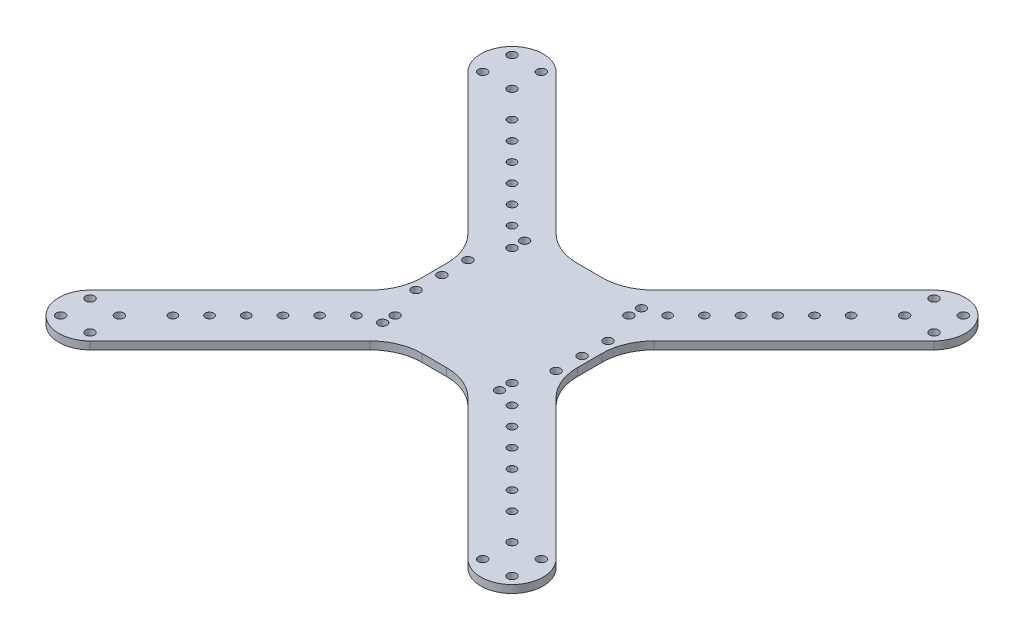
SolidWorks part; units mm, degrees
material "Carbon Fiber"
ref_plane "Front Plane" through (0, 0, 0) normal (0, 0, 1) x (1, 0, 0)
ref_plane "Top Plane" through (0, 0, 0) normal (0, 1, 0) x (1, 0, 0)
ref_plane "Right Plane" through (0, 0, 0) normal (1, 0, 0) x (0, 0, -1)
sketch "Sketch1" plane through (0, 0, 0) normal (0, 1, 0) x (1, 0, 0)
  line L0 (-81.3173, 81.3173) -> (81.3173, -81.3173) construction
  line L1 (-98.425, -98.425) -> (98.425, -98.425) construction
  line L2 (-98.425, -98.425) -> (-98.425, 98.425) construction
  line L3 (-98.425, 98.425) -> (98.425, 98.425) construction
  line L4 (98.425, -98.425) -> (98.425, 98.425) construction
  line L5 (-98.425, -98.425) -> (98.425, 98.425) construction
  line L6 (-98.425, 98.425) -> (98.425, -98.425) construction
  line L7 (-72.832, 89.8026) -> (-13.0294, 30)
  line L8 (-89.8026, 72.832) -> (-30, 13.0294)
  line L9 (0, 98.425) -> (0, -98.425) construction
  line L10 (81.3173, 81.3173) -> (-81.3173, -81.3173) construction
  line L11 (72.832, 89.8026) -> (13.0294, 30)
  line L12 (89.8026, 72.832) -> (30, 13.0294)
  line L13 (-30, -13.0294) -> (-89.8026, -72.832)
  line L14 (-13.0294, -30) -> (13.0294, -30)
  line L15 (-30, -13.0294) -> (-30, 13.0294)
  line L16 (-13.0294, 30) -> (13.0294, 30)
  line L17 (30, -13.0294) -> (30, 13.0294)
  line L18 (-30, -30) -> (30, 30) construction
  line L19 (-30, 30) -> (30, -30) construction
  line L20 (-13.0294, -30) -> (-72.832, -89.8026)
  line L21 (30, -13.0294) -> (89.8026, -72.832)
  line L22 (13.0294, -30) -> (72.832, -89.8026)
  arc A0 (-72.832, 89.8026) -> (-89.8026, 72.832) centre (-81.3173, 81.3173) ccw
  arc A1 (72.832, -89.8026) -> (89.8026, -72.832) centre (81.3173, -81.3173) ccw
  circle A2 centre (-81.3173, 81.3173) radius 8 construction
  circle A3 centre (81.3173, -81.3173) radius 8 construction
  circle A4 centre (-81.3173, -81.3173) radius 8 construction
  circle A5 centre (81.3173, 81.3173) radius 8 construction
  arc A6 (72.832, 89.8026) -> (89.8026, 72.832) centre (81.3173, 81.3173) cw
  arc A7 (-72.832, -89.8026) -> (-89.8026, -72.832) centre (-81.3173, -81.3173) cw
  point P0 (0, 0)
  point P8 (0, 0)
  point P23 (0, 0)
  point P29 (0, 0)
  point P42 (30, 0)
  dimension "D2" = 12
  dimension "D4" = 16
  dimension "D6" = 12
  dimension "D9" = 12
  dimension "D10" = 12
  dimension "D1" = 196.85
  dimension "D3" = 115
  dimension "D5" = 115
  dimension "D8" = 26.0589
  dimension "D11" = 30
  dimension "D12" = 30
extrude "Boss-Extrude1" add sketch "Sketch1" along normal blind 3
fillet "Fillet1" radius 20 8 edges at (-30, 1.5, -13.0294) (-30, 1.5, 13.0294) (-13.0294, 1.5, -30) (13.0294, 1.5, -30) (30, 1.5, 13.0294) (30, 1.5, -13.0294) (13.0294, 1.5, 30) (-13.0294, 1.5, 30)
ref_axis "Axis1" through (0, 6.3, 0) along (0, -1, 0)
ref_plane "Plane1" through (0, 0, 0) normal (-0.7071, 0, 0.7071) x (0, -1, 0)
sketch "Sketch2" plane through (0, 3, 0) normal (0, 1, 0) x (1, 0, 0)
  line L0 (0, 0) -> (-25, 0)
  line L1 (-25, 0) -> (-25, -25)
  line L2 (-25, -25) -> (0, -25)
  line L3 (0, -25) -> (0, 0)
  circle A1 centre (-22.525, -22.525) radius 1.7
  dimension "D4" = 3.4
  dimension "D1" = 25
  dimension "D2" = 22.525
  dimension "D3" = 22.525
extrude "Cut-Extrude1" cut sketch "Sketch2" against normal through all contours A1
pattern_circular "CirPattern1" count 4 over 360 about axis through (0, 0, 0) along (0, 1, 0) of "Cut-Extrude1"
sketch "Sketch3" plane through (0, 3, 0) normal (0, 1, 0) x (1, 0, 0)
  line L0 (0, 0) -> (-89.8026, -89.8026) construction
  circle A0 centre (-30, -30) radius 1.6
  arc A1 (-89.8026, -72.832) -> (-72.832, -89.8026) centre (-81.3173, -81.3173) ccw construction
  dimension "D1" = 3.2
  dimension "D2" = 30
extrude "Cut-Extrude2" cut sketch "Sketch3" against normal through all
pattern_linear "LPattern1" count 6 spacing 10 along (-0.7071, 0, 0.7071) of "Cut-Extrude2"
pattern_circular "CirPattern2" count 4 over 360 about axis through (0, 6.3, 0) along (0, -1, 0) of "LPattern1", "Cut-Extrude2"
sketch "Sketch4" plane through (0, 3, 0) normal (0, 1, 0) x (1, 0, 0)
  line L0 (-89.8026, -72.832) -> (-72.832, -89.8026) construction
  line L1 (-75.6604, -75.6604) -> (-86.9741, -86.9741) construction
  circle A0 centre (-81.3173, -81.3173) radius 8
  circle A1 centre (-86.9741, -86.9741) radius 1.7
  circle A2 centre (-86.9741, -75.6604) radius 1.7
  circle A3 centre (-75.6604, -75.6604) radius 1.7
  circle A4 centre (-75.6604, -86.9741) radius 1.7
  dimension "D1" = 16
  dimension "D2" = 3.4
extrude "Cut-Extrude3" cut sketch "Sketch4" against normal through all contours A0 A2 | A0 A2 | A0 A3 | A0 A3 | A0 A4 | A0 A4 | A0 A1 | A0 A1
pattern_circular "CirPattern3" count 4 over 360 about axis through (0, 0, 0) along (0, 1, 0) of "Cut-Extrude3"
sketch "Sketch5" plane through (0, 3, 0) normal (0, 1, 0) x (1, 0, 0)
  line L0 (-22.525, -22.525) -> (-22.525, 27.375) construction
  line L1 (0, 0) -> (-22.525, 0) construction
  line L2 (-22.525, 0) -> (-22.525, -27.35) construction
  circle A0 centre (-22.525, 27.375) radius 1.7
  circle A1 centre (-22.525, -27.35) radius 1.7
  dimension "D2" = 3.4
  dimension "D5" = 3.4
  dimension "D1" = 49.9
  dimension "D3" = 27.375
  dimension "D4" = 27.35
extrude "Cut-Extrude4" cut sketch "Sketch5" against normal through all contours A0 | A1
mirror "Mirror1" about plane through (0, 0, 0) normal (1, 0, 0) of "Cut-Extrude4"
sketch "Sketch6" plane through (0, 3, 0) normal (0, 1, 0) x (1, 0, 0)
  line L0 (-2.5668, 2.5668) -> (2.5668, -2.5668) construction
  line L1 (-89.8026, 72.832) -> (-72.832, 89.8026) construction
  circle A0 centre (-81.3173, 81.3173) radius 63.5
sketch "Sketch7" plane through (0, 3, 0) normal (0, 1, 0) x (1, 0, 0)
  line L0 (-30, 4.7452) -> (-30, -4.7452) construction
  line L1 (-27, 0) -> (0, 0) construction
  circle A0 centre (-27, 0) radius 1.7
  dimension "D1" = 3.4
  dimension "D2" = 3
extrude "Cut-Extrude5" cut sketch "Sketch7" against normal through all
pattern_linear "LPattern2" count 2 spacing 10 along (0, 0, 1) count 2 spacing 10 along (0, 0, -1) of "Cut-Extrude5"
mirror "Mirror2" about plane through (0, 0, 0) normal (1, 0, 0) of "LPattern2", "Cut-Extrude5"
